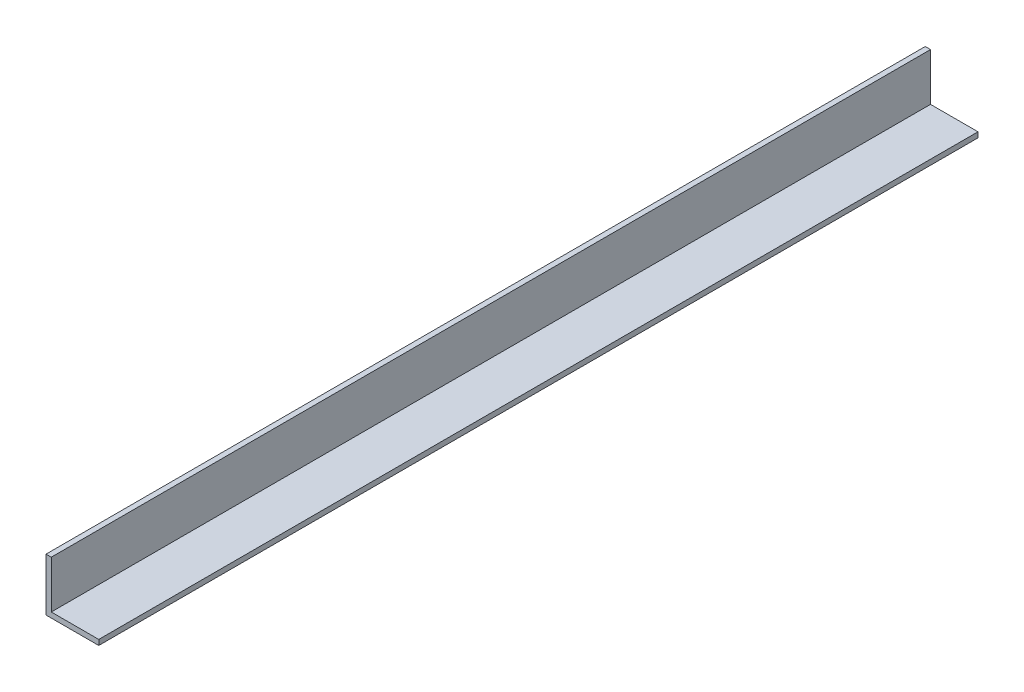
SolidWorks part; units mm, degrees
ref_plane "前视基准面" through (0, 0, 0) normal (0, 0, 1) x (1, 0, 0)
ref_plane "上视基准面" through (0, 0, 0) normal (0, 1, 0) x (1, 0, 0)
ref_plane "右视基准面" through (0, 0, 0) normal (1, 0, 0) x (0, 0, -1)
sketch "草图1" plane through (0, 0, 0) normal (0, 0, 1) x (1, 0, 0)
  line L0 (0, 0) -> (0, 27)
  line L1 (0, 27) -> (-3, 27)
  line L2 (-3, 27) -> (-3, -3)
  line L3 (-3, -3) -> (27, -3)
  line L4 (27, -3) -> (27, 0)
  line L5 (27, 0) -> (0, 0)
extrude "凸台-拉伸1" add sketch "草图1" along normal blind 500
